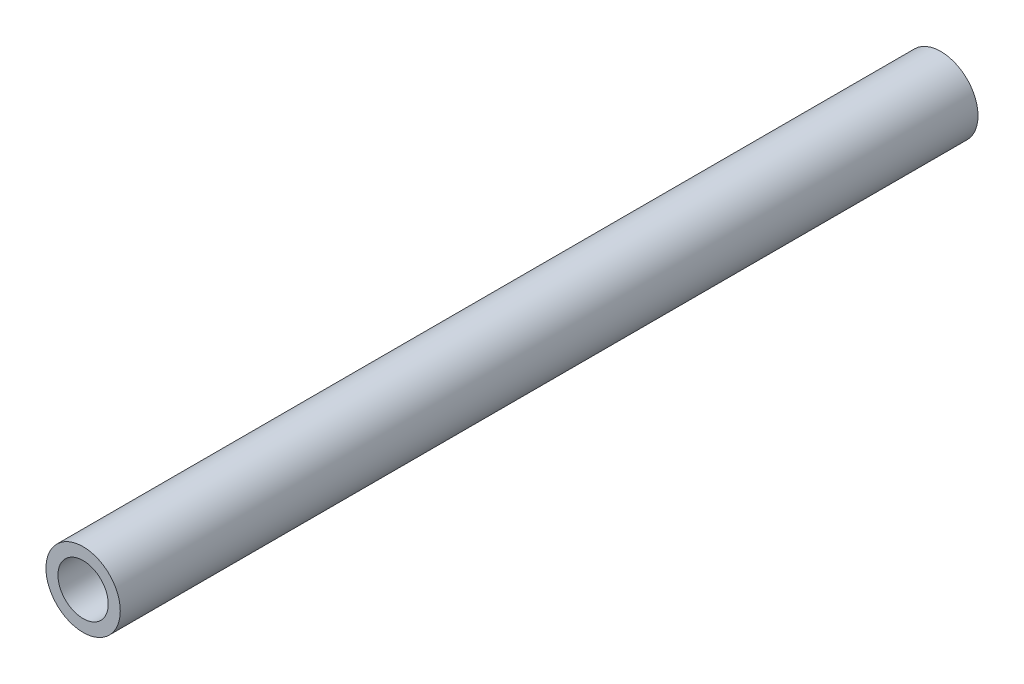
SolidWorks part; units mm, degrees
ref_plane "Front Plane" through (0, 0, 0) normal (0, 0, 1) x (1, 0, 0)
ref_plane "Top Plane" through (0, 0, 0) normal (0, 1, 0) x (1, 0, 0)
ref_plane "Right Plane" through (0, 0, 0) normal (1, 0, 0) x (0, 0, -1)
sketch "Sketch2" plane through (0, 0, 0) normal (0, 0, 1) x (1, 0, 0)
  circle A0 centre (0, 0) radius 4.4
  circle A1 centre (0, 0) radius 6.5
  dimension "D1" = 8.8
  dimension "D2" = 13
extrude "Boss-Extrude1" add sketch "Sketch2" along normal blind 150
